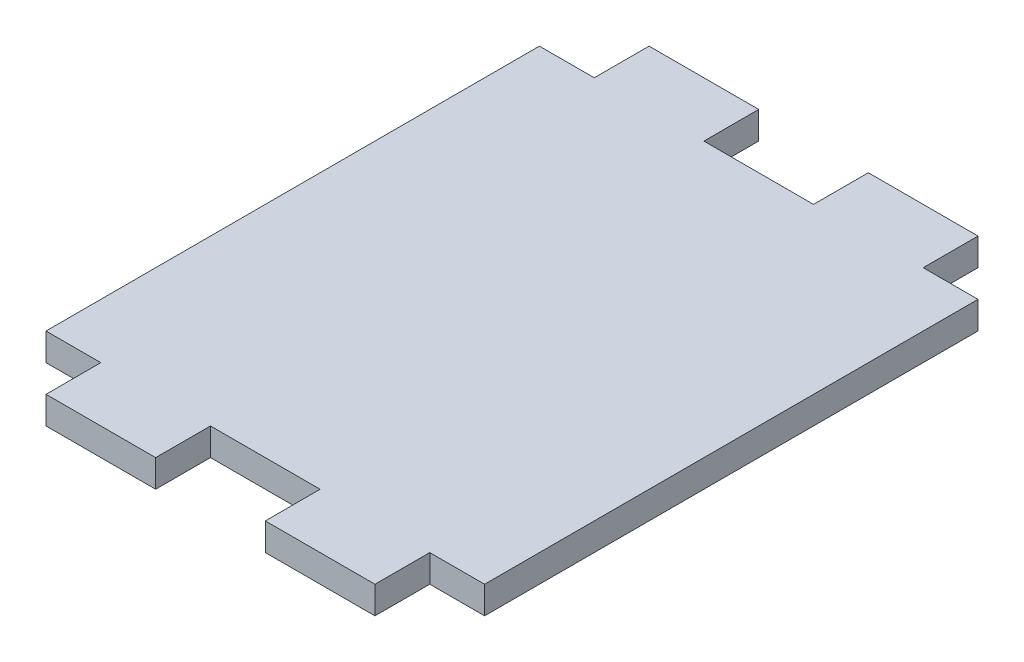
SolidWorks part; units mm, degrees
ref_plane "Front Plane" through (0, 0, 0) normal (0, 0, 1) x (1, 0, 0)
ref_plane "Top Plane" through (0, 0, 0) normal (0, 1, 0) x (1, 0, 0)
ref_plane "Right Plane" through (0, 0, 0) normal (1, 0, 0) x (0, 0, -1)
sketch "Sketch1" plane through (0, 0, 0) normal (0, 0, 1) x (1, 0, 0)
  line L0 (265.9909, 358.7304) -> (265.9909, 355.5554)
  line L1 (265.9909, 355.5554) -> (316.7909, 355.5554)
  line L2 (316.7909, 355.5554) -> (316.7909, 358.7304)
  line L3 (316.7909, 358.7304) -> (265.9909, 358.7304)
  dimension "D1" = 3.175
  dimension "D2" = 50.8
extrude "Boss-Extrude1" add sketch "Sketch1" against normal blind 69.85 contours L3 L0 L1 L2
sketch "Sketch2" plane through (0, 358.7304, 0) normal (0, 1, 0) x (1, 0, 0)
  line L0 (248.8154, 63.5) -> (513.3483, 63.5) construction
  line L1 (265.9909, 69.85) -> (272.3409, 69.85)
  line L2 (265.9909, 69.85) -> (265.9909, 63.5)
  line L3 (265.9909, 63.5) -> (272.3409, 63.5)
  line L4 (272.3409, 69.85) -> (272.3409, 63.5)
  line L5 (316.7909, 69.85) -> (265.9909, 69.85) construction
  line L6 (316.7909, 69.85) -> (310.4409, 69.85)
  line L7 (316.7909, 69.85) -> (316.7909, 63.5)
  line L8 (316.7909, 63.5) -> (310.4409, 63.5)
  line L9 (310.4409, 69.85) -> (310.4409, 63.5)
  line L10 (285.0409, 69.85) -> (297.7409, 69.85)
  line L11 (285.0409, 69.85) -> (285.0409, 63.5)
  line L12 (285.0409, 63.5) -> (297.7409, 63.5)
  line L13 (297.7409, 69.85) -> (297.7409, 63.5)
  line L14 (513.3483, 6.35) -> (248.8154, 6.35) construction
  line L15 (265.9909, 0) -> (272.3409, 0)
  line L16 (265.9909, 0) -> (265.9909, 6.35)
  line L17 (265.9909, 6.35) -> (272.3409, 6.35)
  line L18 (272.3409, 0) -> (272.3409, 6.35)
  line L19 (316.7909, 0) -> (265.9909, 0) construction
  line L20 (285.0409, 0) -> (297.7409, 0)
  line L21 (285.0409, 0) -> (285.0409, 6.35)
  line L22 (285.0409, 6.35) -> (297.7409, 6.35)
  line L23 (297.7409, 0) -> (297.7409, 6.35)
  line L25 (316.7909, 0) -> (310.4409, 0)
  line L26 (316.7909, 0) -> (316.7909, 6.35)
  line L27 (316.7909, 6.35) -> (310.4409, 6.35)
  line L28 (310.4409, 0) -> (310.4409, 6.35)
  dimension "D1" = 6.35
  dimension "D2" = 12.7
  dimension "D3" = 6.35
  dimension "D4" = 12.7
  dimension "D5" = 6.35
  dimension "D6" = 12.7
  dimension "D7" = 6.35
  dimension "D8" = 12.7
extrude "Cut-Extrude1" cut sketch "Sketch2" against normal through all
